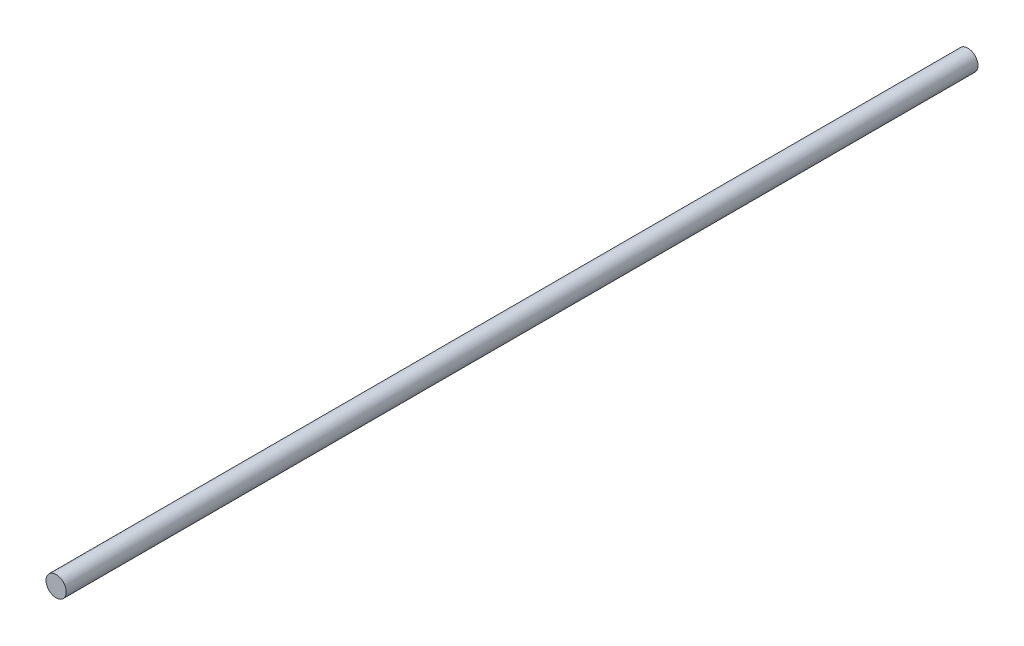
SolidWorks part; units mm, degrees
material "AISI 304"
ref_plane "前视基准面" through (0, 0, 0) normal (0, 0, 1) x (1, 0, 0)
ref_plane "上视基准面" through (0, 0, 0) normal (0, 1, 0) x (1, 0, 0)
ref_plane "右视基准面" through (0, 0, 0) normal (1, 0, 0) x (0, 0, -1)
sketch "草图1" plane through (0, 0, 0) normal (0, 0, 1) x (1, 0, 0)
  circle A0 centre (0, 0) radius 0.5
  dimension "D1" = 1
extrude "凸台-拉伸1" add sketch "草图1" along normal blind 45
